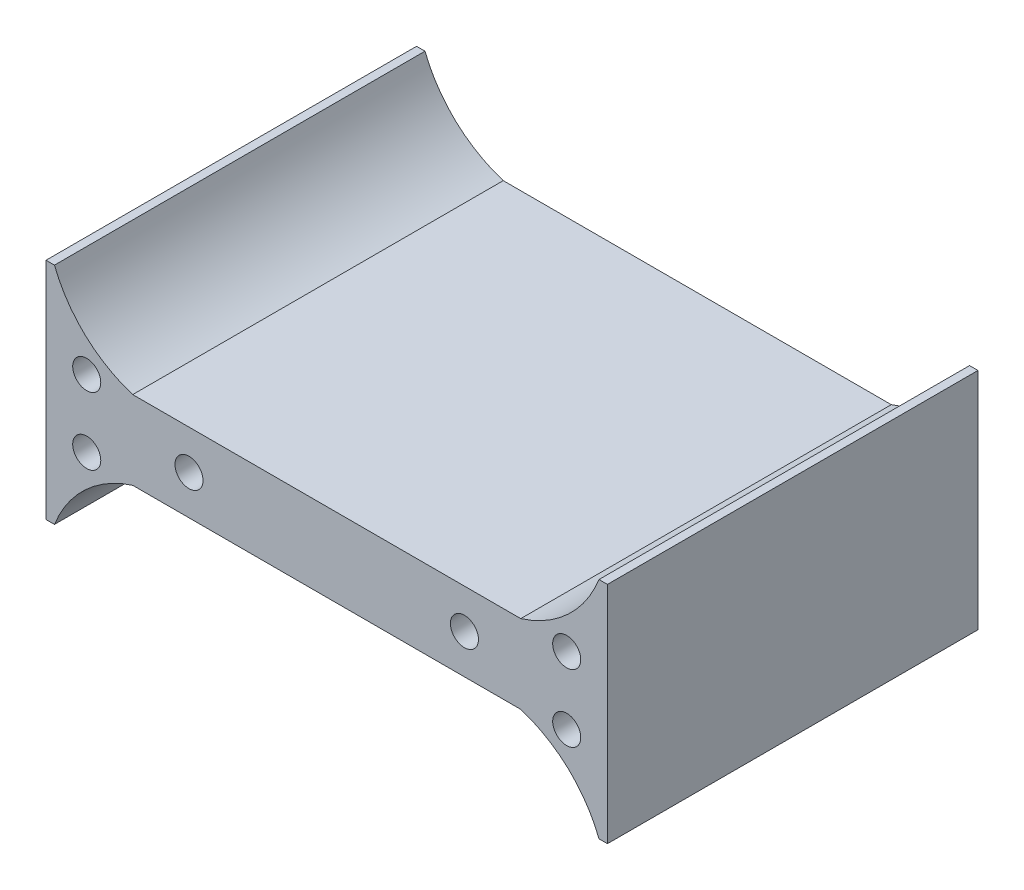
SolidWorks part; units mm, degrees
ref_plane "前视基准面" through (0, 0, 0) normal (0, 0, 1) x (1, 0, 0)
ref_plane "上视基准面" through (0, 0, 0) normal (0, 1, 0) x (1, 0, 0)
ref_plane "右视基准面" through (0, 0, 0) normal (1, 0, 0) x (0, 0, -1)
sketch "草图1" plane through (0, 0, 0) normal (0, 0, 1) x (1, 0, 0)
  circle A0 centre (25, 39) radius 10
  circle A1 centre (11, 11) radius 10
  circle A2 centre (39, 11) radius 10
  line B0 (0, 50) -> (50, 50)
  line B1 (0, 0) -> (0, 50)
  line B2 (50, 0) -> (0, 0)
  circle B3 centre (19, 17.5) radius 1.25
  circle B4 centre (25, 39) radius 3.25
  circle B5 centre (11, 11) radius 3.25
  circle B6 centre (39, 11) radius 3.25
  line B7 (50, 50) -> (50, 0)
  circle B8 centre (31, 17.5) radius 1.25
  circle B9 centre (19, 5.5) radius 1.25
  dimension "D1" = 20
sketch_block_instance "bottom-4"
sketch_block "bottom"
sketch "草图3" plane through (0, 0, 0) normal (0, 0, 1) x (1, 0, 0)
  line L17 (0, 0) -> (0, 50) construction
  line L18 (0, 28.5) -> (50, 28.5)
  line L19 (0, 28.5) -> (0, 21.5)
  line L20 (0, 21.5) -> (50, 21.5)
  line L21 (50, 28.5) -> (50, 21.5)
  line L22 (50, 50) -> (50, 0) construction
  line L23 (25, 50) -> (25, 28.5) construction
  line L24 (0, 50) -> (50, 50) construction
  line L25 (25, 21.5) -> (25, 0) construction
  line L26 (50, 0) -> (0, 0) construction
  dimension "D1" = 7
extrude "凸台-拉伸1" add sketch "草图3" along normal blind 33
sketch "草图4" plane through (0, 0, 0) normal (0, 0, -1) x (-1, 0, 0)
  line L0 (-50, 21.5) -> (-50, 11)
  line L1 (-50, 21.5) -> (-42.2787, 21.5)
  line L2 (0, 21.5) -> (-50, 21.5) construction
  line L3 (-7.7213, 21.5) -> (0, 21.5)
  line L4 (0, 21.5) -> (0, 11)
  line L5 (-50, 25) -> (49950, 25) construction
  line L6 (-50, 50) -> (-50, 0) construction
  line L7 (0, 28.5) -> (0, 39)
  line L8 (-7.7213, 28.5) -> (0, 28.5)
  line L9 (-50, 28.5) -> (-42.2787, 28.5)
  line L10 (-50, 28.5) -> (-50, 39)
  arc A1 (-42.2787, 21.5) -> (-50, 11) centre (-39, 11) ccw
  arc A2 (0, 11) -> (-7.7213, 21.5) centre (-11, 11) ccw
  arc A3 (0, 39) -> (-7.7213, 28.5) centre (-11, 39) cw
  arc A4 (-42.2787, 28.5) -> (-50, 39) centre (-39, 39) cw
  point P19 (-50, 25)
extrude "凸台-拉伸2" add sketch "草图4" against normal blind 33
sketch "草图5" plane through (0, 0, 0) normal (0, 0, -1) x (-1, 0, 0)
  line L0 (-46.3725, 28) -> (-46.3725, 22) construction
  line L5 (-37.2645, 25) -> (-50, 25) construction
  line L7 (-50, 50) -> (-50, 0) construction
  line L8 (-25, 21.5) -> (-25, -49978.5) construction
  circle A2 centre (-46.3725, 28) radius 1.25
  circle A3 centre (-46.3725, 22) radius 1.25
  circle A4 centre (-37.2645, 25) radius 1.25
  circle A5 centre (-3.6275, 22) radius 1.25
  circle A6 centre (-3.6275, 28) radius 1.25
  circle A7 centre (-12.7355, 25) radius 1.25
  dimension "D1" = 2.5
  dimension "D2" = 3
  dimension "D3" = 6
extrude "切除-拉伸1" cut sketch "草图5" against normal blind 8
sketch "草图6" plane through (0, 0, 0) normal (0, 0, -1) x (-1, 0, 0)
  line L0 (0, 39) -> (0, 11) construction
  line L1 (-50, 39) -> (0, 39)
  line L2 (-50, 39) -> (-50, 35)
  line L3 (-50, 35) -> (0, 35)
  line L4 (0, 39) -> (0, 35)
  line L6 (-50, 11) -> (0, 11)
  line L7 (-50, 11) -> (-50, 15)
  line L8 (-50, 15) -> (0, 15)
  line L9 (0, 11) -> (0, 15)
  dimension "D1" = 4
extrude "切除-拉伸2" cut sketch "草图6" against normal blind 40
sketch "草图7" plane through (0, 0, 33) normal (0, 0, 1) x (1, 0, 0)
  circle A0 centre (3.6275, 28) radius 1.25
  circle A1 centre (3.6275, 22) radius 1.25
  circle A2 centre (12.7355, 25) radius 1.25
  circle A3 centre (46.3725, 22) radius 1.25
  circle A4 centre (46.3725, 28) radius 1.25
  circle A5 centre (37.2645, 25) radius 1.25
extrude "切除-拉伸3" cut sketch "草图7" against normal blind 8
